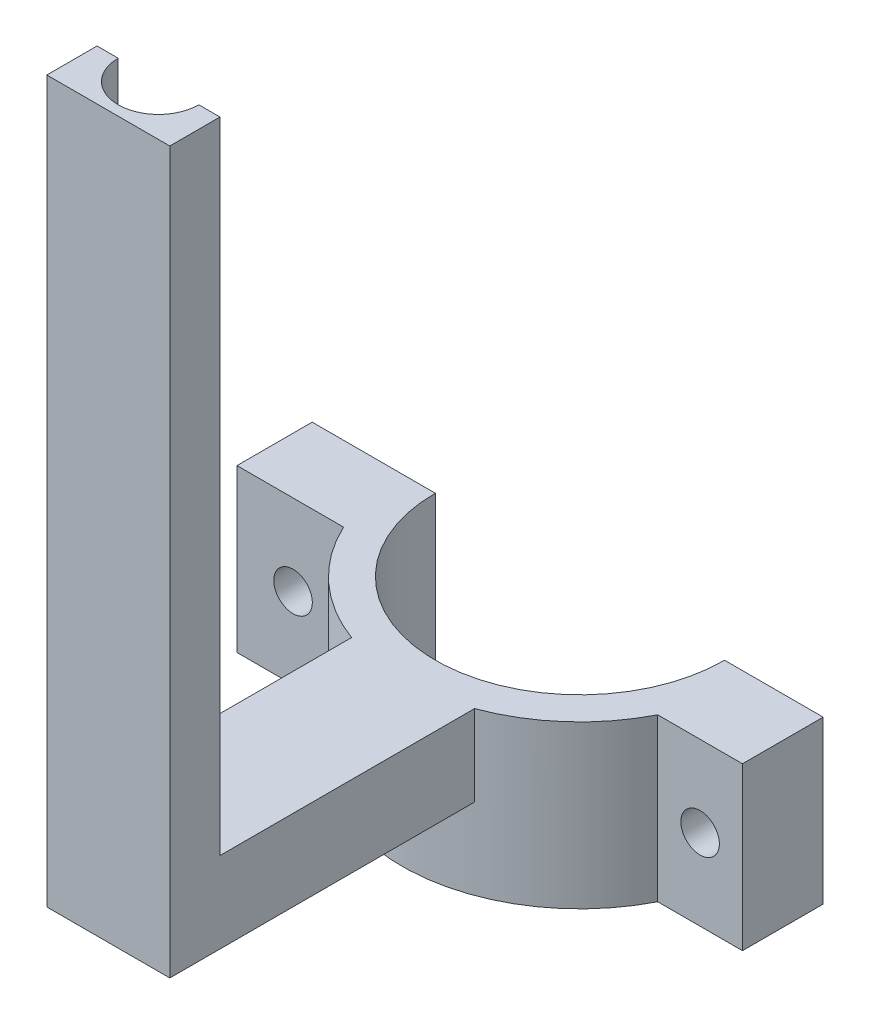
SolidWorks part; units mm, degrees
ref_plane "前基準面" through (0, 0, 0) normal (0, 0, 1) x (1, 0, 0)
ref_plane "上基準面" through (0, 0, 0) normal (0, 1, 0) x (1, 0, 0)
ref_plane "右基準面" through (0, 0, 0) normal (1, 0, 0) x (0, 0, -1)
sketch "草圖1" plane through (0, 0, 0) normal (0, 1, 0) x (1, 0, 0)
  circle A0 centre (0, 0) radius 14.34
  dimension "D1" = 28.68
extrude "伸長-薄件1" add sketch "草圖1" along normal blind 16.05 thin
ref_plane "平面1" through (17.75, 0, 0) normal (1, 0, 0) x (0, 0, -1)
sketch "草圖2" plane through (17.75, 0, 0) normal (1, 0, 0) x (0, 0, -1)
  line L0 (0, -983.95) -> (0, 49016.05) construction
  line L1 (14.34, 16.05) -> (-14.34, 16.05) construction
  line L2 (-1017.63, 8.025) -> (48982.37, 8.025) construction
  line L3 (-17.63, 16.05) -> (-17.63, 0) construction
  line L5 (-8, 16.05) -> (8, 16.05)
  line L6 (-8, 16.05) -> (-8, 0)
  line L7 (-8, 0) -> (8, 0)
  line L8 (8, 16.05) -> (8, 0)
  line L9 (-8, 16.05) -> (8, 0) construction
  line L10 (-8, 0) -> (8, 16.05) construction
  point P5 (0, 16.05)
  point P6 (0, 8.025)
  point P10 (-17.63, 8.025)
  dimension "D1" = 0
  dimension "D2" = 16
extrude "填料-伸長1" add sketch "草圖2" along normal blind 9.77 and the other way blind 3
sketch "草圖3" plane through (0, 16.05, 0) normal (0, 1, 0) x (1, 0, 0)
  line L0 (14.34, 0) -> (27.52, 0) construction
  line L1 (27.52, 8) -> (27.52, -8) construction
  line L2 (15.7104, -8) -> (27.52, -8) construction
  line L3 (27.52, 8) -> (24.11, 8)
  line L4 (27.52, 8) -> (27.52, -8)
  line L5 (27.52, -8) -> (24.11, -8)
  line L6 (24.11, 8) -> (24.11, -8)
  circle A0 centre (0, 0) radius 14.34 construction
  dimension "D1" = 3.41
extrude "除料-伸長1" cut sketch "草圖3" against normal through all
sketch "草圖4" plane through (0, 0, 8) normal (0, 0, 1) x (1, 0, 0)
  line L0 (19.9102, -983.95) -> (19.9102, 49016.05) construction
  line L1 (15.7104, 16.05) -> (24.11, 16.05) construction
  line L2 (-984.2896, 8.025) -> (49015.7104, 8.025) construction
  line L3 (15.7104, 0) -> (15.7104, 16.05) construction
  circle A0 centre (19.9102, 8.025) radius 1.91
  point P5 (19.9102, 16.05)
  point P10 (15.7104, 8.025)
  dimension "D1" = 3.82
extrude "除料-伸長2" cut sketch "草圖4" against normal through all
ref_plane "平面2" through (0, 0, 17.75) normal (0, 0, 1) x (1, 0, 0)
sketch "草圖5" plane through (0, 0, 17.75) normal (0, 0, 1) x (1, 0, 0)
  line L0 (-1017.63, 8.025) -> (48982.37, 8.025) construction
  line L1 (-17.63, 16.05) -> (-17.63, 0) construction
  line L2 (0, -983.95) -> (0, 49016.05) construction
  line L3 (14.34, 16.05) -> (-14.34, 16.05) construction
  line L5 (-6.095, 16.2886) -> (6.095, 16.2886)
  line L6 (-6.095, 16.2886) -> (-6.095, 8.025)
  line L7 (-6.095, 8.025) -> (6.095, 8.025)
  line L8 (6.095, 16.2886) -> (6.095, 8.025)
  line L9 (-6.095, 16.2886) -> (6.095, 8.025) construction
  line L10 (-6.095, 8.025) -> (6.095, 16.2886) construction
  point P5 (-17.63, 8.025)
  point P6 (0, 12.1568)
  point P10 (0, 16.05)
  dimension "D1" = 12.19
extrude "填料-伸長2" add sketch "草圖5" along normal blind 4 and the other way blind 2.77
sketch "草圖6" plane through (0, 16.2886, 0) normal (0, 1, 0) x (1, 0, 0)
  line L1 (-6.095, -14.98) -> (6.095, -14.98)
  line L2 (-6.095, -14.98) -> (-6.095, -21.75)
  line L3 (-6.095, -21.75) -> (6.095, -21.75)
  line L4 (6.095, -14.98) -> (6.095, -21.75)
extrude "填料-伸長3" add sketch "草圖6" along normal blind 63
sketch "草圖8" plane through (0, 79.2886, 0) normal (0, 1, 0) x (1, 0, 0)
  line L1 (-6.095, -21.75) -> (6.095, -21.75)
  line L2 (-6.095, -21.75) -> (-6.095, -14.98)
  line L3 (-6.095, -14.98) -> (6.095, -14.98)
  line L4 (6.095, -21.75) -> (6.095, -14.98)
extrude "填料-伸長4" add sketch "草圖8" along normal blind 0.16
ref_plane "平面3" through (-17.75, 0, 0) normal (1, 0, 0) x (0, 0, -1)
sketch "草圖12" plane through (-17.75, 0, 0) normal (1, 0, 0) x (0, 0, -1)
  line L0 (0.5435, -983.95) -> (0.5435, 49016.05) construction
  line L1 (17.63, 16.05) -> (-16.5429, 16.05) construction
  line L2 (-982.37, 8.025) -> (49017.63, 8.025) construction
  line L3 (17.63, 0) -> (17.63, 16.05) construction
  line L5 (8.5435, 16.05) -> (-7.4565, 16.05)
  line L6 (8.5435, 16.05) -> (8.5435, 0)
  line L7 (8.5435, 0) -> (-7.4565, 0)
  line L8 (-7.4565, 16.05) -> (-7.4565, 0)
  line L9 (8.5435, 16.05) -> (-7.4565, 0) construction
  line L10 (8.5435, 0) -> (-7.4565, 16.05) construction
  point P5 (0.5435, 16.05)
  point P6 (0.5435, 8.025)
  point P10 (17.63, 8.025)
  dimension "D1" = 0
  dimension "D2" = 16
extrude "填料-伸長5" add sketch "草圖12" along normal blind 3.16 and the other way blind 10
sketch "草圖13" plane through (0, 16.05, 0) normal (0, 1, 0) x (1, 0, 0)
  line L0 (-14.34, 0) -> (-27.75, 0) construction
  line L1 (-27.75, 8.5435) -> (-27.75, -7.4565) construction
  line L2 (-27.75, -7.4565) -> (-15.9755, -7.4565) construction
  line L3 (-27.75, 8.5435) -> (-26.54, 8.5435)
  line L4 (-27.75, 8.5435) -> (-27.75, -7.4565)
  line L5 (-27.75, -7.4565) -> (-26.54, -7.4565)
  line L6 (-26.54, 8.5435) -> (-26.54, -7.4565)
  circle A0 centre (0, 0) radius 14.34 construction
  dimension "D1" = 1.21
extrude "除料-伸長3" cut sketch "草圖13" against normal through all
sketch "草圖14" plane through (0, 0, -8.5435) normal (0, 0, -1) x (-1, 0, 0)
  line L0 (20.9808, -983.95) -> (20.9808, 49016.05) construction
  line L1 (26.54, 16.05) -> (15.4216, 16.05) construction
  line L2 (-973.46, 8.025) -> (49026.54, 8.025) construction
  line L3 (26.54, 0) -> (26.54, 16.05) construction
  circle A0 centre (20.9808, 8.025) radius 1.91
  point P5 (20.9808, 16.05)
  point P10 (26.54, 8.025)
  dimension "D1" = 3.82
extrude "除料-伸長4" cut sketch "草圖14" against normal through all
sketch "草圖15" plane through (0, 79.4486, 0) normal (0, 1, 0) x (1, 0, 0)
  line L0 (6.095, -14.98) -> (-6.095, -14.98) construction
  circle A0 centre (0, -14.98) radius 4.05
  dimension "D1" = 8.1
extrude "除料-伸長5" cut sketch "草圖15" against normal blind 24
sketch "草圖16" plane through (0, 16.05, 0) normal (0, 1, 0) x (1, 0, 0)
  line L0 (24.11, 8) -> (24.11, -8) construction
  line L1 (24.11, 0) -> (-32.2905, 0)
  line L2 (24.11, 0) -> (24.11, 19.935)
  line L3 (24.11, 19.935) -> (-32.2905, 19.935)
  line L4 (-32.2905, 0) -> (-32.2905, 19.935)
extrude "除料-伸長6" cut sketch "草圖16" against normal through all
sketch "草圖17" plane through (0, 0, 21.75) normal (0, 0, 1) x (1, 0, 0)
  line L1 (-6.095, 8.025) -> (6.095, 8.025)
  line L2 (-6.095, 8.025) -> (-6.095, 79.4486)
  line L3 (-6.095, 79.4486) -> (6.095, 79.4486)
  line L4 (6.095, 8.025) -> (6.095, 79.4486)
extrude "填料-伸長7" add sketch "草圖17" along normal blind 25
sketch "草圖18" plane through (-6.095, 0, 0) normal (-1, 0, 0) x (0, 0, 1)
  line L0 (14.98, 79.4486) -> (46.75, 79.4486) construction
  line L1 (14.98, 16.05) -> (41.7734, 16.05)
  line L2 (14.98, 16.05) -> (14.98, 79.4486)
  line L3 (14.98, 79.4486) -> (41.7734, 79.4486)
  line L4 (41.7734, 16.05) -> (41.7734, 79.4486)
extrude "除料-伸長7" cut sketch "草圖18" against normal blind 25
sketch "草圖19" plane through (0, 79.4486, 0) normal (0, 1, 0) x (1, 0, 0)
  line L0 (6.095, -41.7734) -> (-6.095, -41.7734) construction
  circle A0 centre (0, -41.7734) radius 4
  dimension "D1" = 8
extrude "除料-伸長8" cut sketch "草圖19" against normal blind 24
